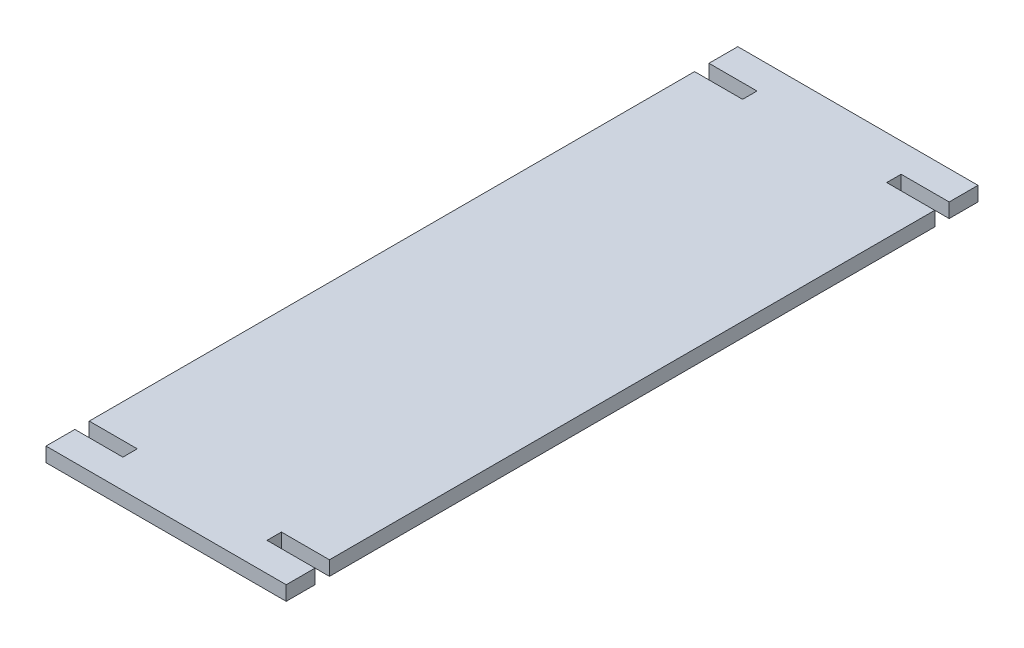
SolidWorks part; units mm, degrees
ref_plane "Front" through (0, 0, 0) normal (0, 0, 1) x (1, 0, 0)
ref_plane "Top" through (0, 0, 0) normal (0, 1, 0) x (1, 0, 0)
ref_plane "Right" through (0, 0, 0) normal (1, 0, 0) x (0, 0, -1)
sketch "Sketch1" plane through (0, 0, 0) normal (0, 1, 0) x (1, 0, 0)
  line L1 (0, 0) -> (-100, 0)
  line L2 (0, 0) -> (0, 288)
  line L3 (0, 288) -> (-100, 288)
  line L4 (-100, 0) -> (-100, 288)
  dimension "D1" = 288
  dimension "D2" = 100
extrude "Boss-Extrude1" add sketch "Sketch1" along normal blind 6
sketch "Sketch2" plane through (0, 6, 0) normal (0, 1, 0) x (1, 0, 0)
  line L0 (-100, 288) -> (-100, 0) construction
  line L1 (-100, 276) -> (-80, 276)
  line L2 (-100, 276) -> (-100, 270)
  line L3 (-100, 270) -> (-80, 270)
  line L4 (-80, 276) -> (-80, 270)
  line L5 (0, 288) -> (-100, 288) construction
  dimension "D1" = 6
  dimension "D2" = 20
  dimension "D3" = 12
extrude "Cut-Extrude1" cut sketch "Sketch2" against normal through all
pattern_linear "LPattern1" count 2 spacing 258 along (0, 0, 1) count 2 spacing 80 along (1, 0, 0) of "Cut-Extrude1"
